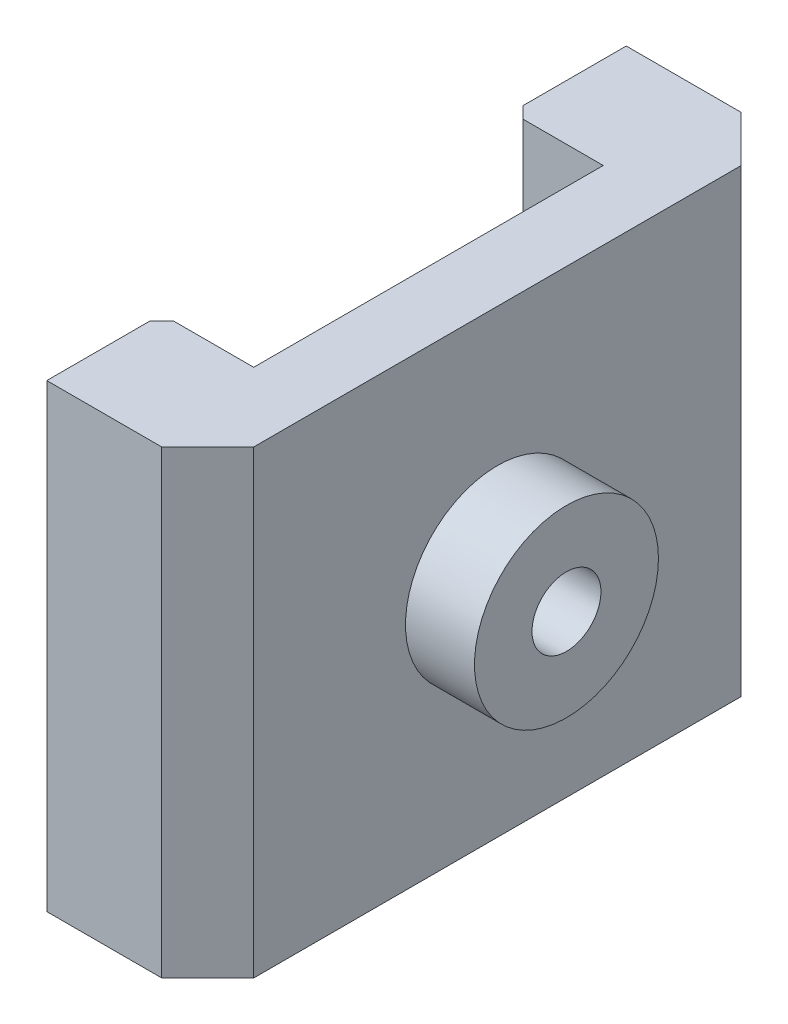
SolidWorks part; units mm, degrees
material "PLA"
ref_plane "前视基准面" through (0, 0, 0) normal (0, 0, 1) x (1, 0, 0)
ref_plane "上视基准面" through (0, 0, 0) normal (0, 1, 0) x (1, 0, 0)
ref_plane "右视基准面" through (0, 0, 0) normal (1, 0, 0) x (0, 0, -1)
sketch "草图1" plane through (0, 0, 0) normal (0, 1, 0) x (1, 0, 0)
  line L0 (-7, 12.6) -> (0, 12.6)
  line L1 (0, 12.6) -> (0, -12.6)
  line L2 (0, -12.6) -> (-7, -12.6)
  line L3 (-7, -12.6) -> (-7, -7.6)
  line L4 (-7, -7.6) -> (-3, -7.6)
  line L5 (-3, -7.6) -> (-3, 7.6)
  line L6 (-3, 7.6) -> (-7, 7.6)
  line L7 (-7, 7.6) -> (-7, 12.6)
  dimension "D1" = 15.2
  dimension "D2" = 5
  dimension "D3" = 3
  dimension "D4" = 4
extrude "凸台-拉伸1" add sketch "草图1" along normal blind 20
chamfer "倒角1" distance 2 angle 45 2 edges at (0, 10, -12.6) (0, 10, 12.6)
sketch "草图2" plane through (0, 0, 0) normal (1, 0, 0) x (0, 0, -1)
  line L0 (-12.6, 0) -> (-12.6, 20) construction
  circle A0 centre (0, 10) radius 4
  point P7 (-12.6, 10)
  dimension "D1" = 8
chamfer "倒角3" distance 0.5 angle 45 2 edges at (-7, 10, -7.6) (-7, 10, 7.6)
extrude "凸台-拉伸2" add sketch "草图2" along normal blind 3
sketch "草图3" plane through (3, 0, 0) normal (1, 0, 0) x (0, 0, -1)
  circle A0 centre (0, 10) radius 1.5
extrude "切除-拉伸1" cut sketch "草图3" against normal blind 10
